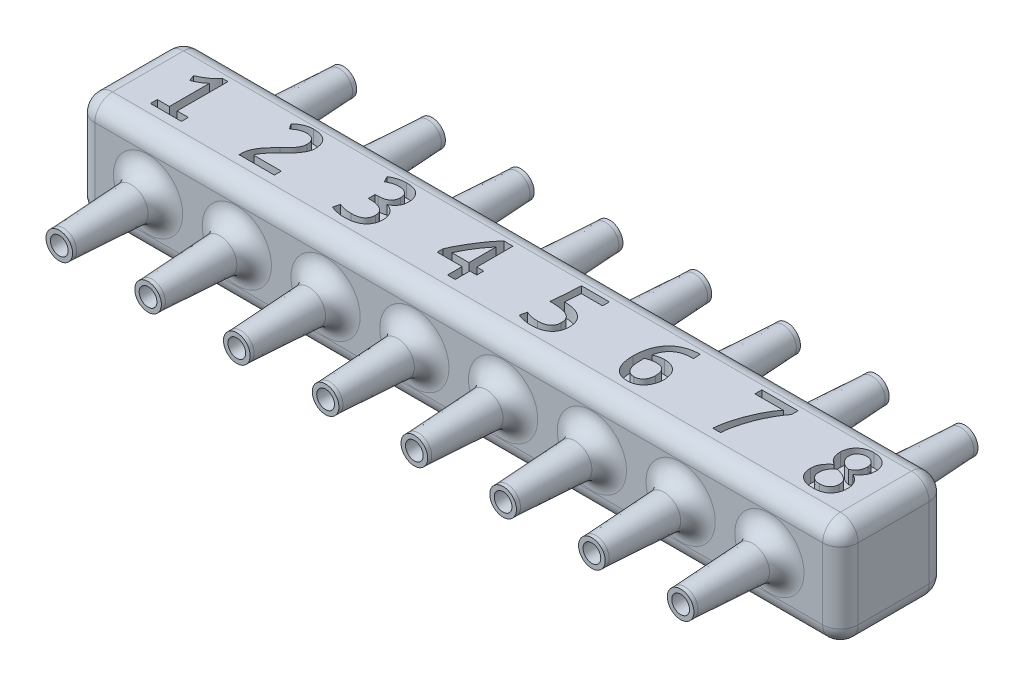
SolidWorks part; units mm, degrees
ref_plane "Front Plane" through (0, 0, 0) normal (0, 0, 1) x (1, 0, 0)
ref_plane "Top Plane" through (0, 0, 0) normal (0, 1, 0) x (1, 0, 0)
ref_plane "Right Plane" through (0, 0, 0) normal (1, 0, 0) x (0, 0, -1)
sketch "Sketch1" plane through (0, 0, 0) normal (0, 1, 0) x (1, 0, 0)
  line L1 (43, -6) -> (-43, -6)
  line L2 (43, -6) -> (43, 6)
  line L3 (43, 6) -> (-43, 6)
  line L4 (-43, -6) -> (-43, 6)
  line L5 (43, -6) -> (-43, 6) construction
  line L6 (43, 6) -> (-43, -6) construction
  point P0 (0, 0)
  dimension "D1" = 12
  dimension "D2" = 86
extrude "Boss-Extrude1" add sketch "Sketch1" along normal mid plane 12
sketch "Sketch2" plane through (0, 0, 6) normal (0, 0, 1) x (1, 0, 0)
  line L0 (-35, 0) -> (35, 0) construction
  line L1 (-43, 6) -> (-43, -6) construction
  line L2 (43, 6) -> (43, -6) construction
  circle A0 centre (-35, 0) radius 1
  circle A1 centre (-25, 0) radius 1
  circle A2 centre (-15, 0) radius 1
  circle A3 centre (-5, 0) radius 1
  circle A4 centre (5, 0) radius 1
  circle A5 centre (15, 0) radius 1
  circle A6 centre (25, 0) radius 1
  circle A7 centre (35, 0) radius 1
  point P7 (-43, 0)
  dimension "D3" = 2
  dimension "D1" = 8
  dimension "D2" = 8
  dimension "D4" = 8
extrude "Cut-Extrude1" cut sketch "Sketch2" against normal through all
sketch "Sketch3" plane through (0, 0, 6) normal (0, 0, 1) x (1, 0, 0)
  circle A0 centre (-35, 0) radius 1 construction
  circle A1 centre (-35, 0) radius 1
  circle A2 centre (-35, 0) radius 2
  circle A3 centre (35, 0) radius 1 construction
  circle A4 centre (25, 0) radius 1 construction
  circle A5 centre (15, 0) radius 1 construction
  circle A6 centre (5, 0) radius 1 construction
  circle A7 centre (-5, 0) radius 1 construction
  circle A8 centre (-15, 0) radius 1 construction
  circle A9 centre (-25, 0) radius 1 construction
  circle A10 centre (35, 0) radius 1
  circle A11 centre (25, 0) radius 1
  circle A12 centre (15, 0) radius 1
  circle A13 centre (5, 0) radius 1
  circle A14 centre (-5, 0) radius 1
  circle A15 centre (-15, 0) radius 1
  circle A16 centre (-25, 0) radius 1
  circle A17 centre (-25, 0) radius 2
  circle A18 centre (-15, 0) radius 2
  circle A19 centre (-5, 0) radius 2
  circle A20 centre (5, 0) radius 2
  circle A21 centre (15, 0) radius 2
  circle A22 centre (25, 0) radius 2
  circle A23 centre (35, 0) radius 2
  dimension "D1" = 1
extrude "Boss-Extrude2" add sketch "Sketch3" along normal blind 10 draft 3
sketch "Sketch4" plane through (0, 0, 6) normal (0, 0, 1) x (1, 0, 0)
  circle A0 centre (-35, 0) radius 1.5 construction
  circle A1 centre (-35, 0) radius 1 construction
  circle A2 centre (-35, 0) radius 1.5
  circle A3 centre (-35, 0) radius 1
  circle A4 centre (-25, 0) radius 1.5 construction
  circle A5 centre (-15, 0) radius 1.5 construction
  circle A6 centre (-5, 0) radius 1.5 construction
  circle A7 centre (5, 0) radius 1.5 construction
  circle A8 centre (15, 0) radius 1.5 construction
  circle A9 centre (25, 0) radius 1.5 construction
  circle A10 centre (35, 0) radius 1.5 construction
  circle A11 centre (35, 0) radius 1 construction
  circle A12 centre (25, 0) radius 1 construction
  circle A13 centre (15, 0) radius 1 construction
  circle A14 centre (5, 0) radius 1 construction
  circle A15 centre (-5, 0) radius 1 construction
  circle A16 centre (-15, 0) radius 1 construction
  circle A17 centre (-25, 0) radius 1 construction
  circle A18 centre (-25, 0) radius 1.5
  circle A19 centre (-15, 0) radius 1.5
  circle A20 centre (-5, 0) radius 1.5
  circle A21 centre (5, 0) radius 1.5
  circle A22 centre (15, 0) radius 1.5
  circle A23 centre (25, 0) radius 1.5
  circle A24 centre (35, 0) radius 1.5
  circle A25 centre (35, 0) radius 1
  circle A26 centre (25, 0) radius 1
  circle A27 centre (15, 0) radius 1
  circle A28 centre (5, 0) radius 1
  circle A29 centre (-5, 0) radius 1
  circle A30 centre (-15, 0) radius 1
  circle A31 centre (-25, 0) radius 1
extrude "Boss-Extrude3" add sketch "Sketch4" along normal blind 10
mirror "Mirror5" about plane through (0, 0, 0) normal (0, 0, 1) of "Boss-Extrude2", "Boss-Extrude3"
fillet "Fillet1" radius 2 16 edges at (-33, 0, 6) (37, 0, 6) (27, 0, 6) (17, 0, 6) (7, 0, 6) (-3, 0, 6) (-13, 0, 6) (-23, 0, 6) (37, 0, -6) (27, 0, -6) (17, 0, -6) (7, 0, -6) (-3, 0, -6) (-13, 0, -6) (-23, 0, -6) (-33, 0, -6)
fillet "Fillet2" radius 2 12 edges at (43, 0, 6) (43, 0, -6) (-43, 0, -6) (-43, 0, 6) (0, -6, 6) (43, -6, 0) (0, -6, -6) (-43, -6, 0) (0, 6, -6) (43, 6, 0) (0, 6, 6) (-43, 6, 0)
sketch "Sketch5" plane through (0, 6, 0) normal (0, 1, 0) x (1, 0, 0)
  line L0 (-38.8979, -3) -> (38.8979, -3) construction
  line L2 (41, -6) -> (-41, -6) construction
  text T0 "1 2 3 4 5 6 7 8" font "Ubuntu Mono" height 6.5
  point P4 (0, 0)
  dimension "D1" = 3
extrude "Cut-Extrude2" cut sketch "Sketch5" against normal blind 1.5
